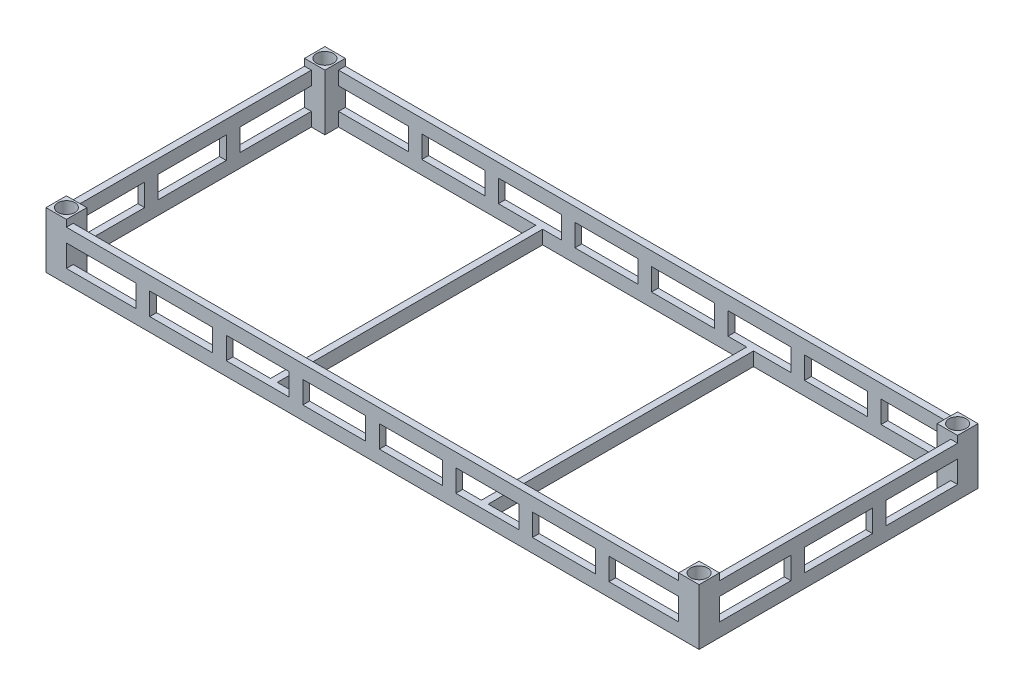
SolidWorks part; units mm, degrees
ref_plane "Front Plane" through (0, 0, 0) normal (0, 0, 1) x (1, 0, 0)
ref_plane "Top Plane" through (0, 0, 0) normal (0, 1, 0) x (1, 0, 0)
ref_plane "Right Plane" through (0, 0, 0) normal (1, 0, 0) x (0, 0, -1)
sketch "Sketch1" plane through (0, 0, 0) normal (0, 1, 0) x (1, 0, 0)
  line L0 (0, 820) -> (60, 820)
  line L1 (0, 0) -> (1920, 0)
  line L2 (0, 0) -> (0, 820)
  line L3 (0, 820) -> (1920, 820)
  line L4 (1920, 0) -> (1920, 820)
  line L5 (60, 820) -> (60, 760)
  line L6 (60, 760) -> (0, 760)
  line L7 (0, 760) -> (0, 765)
  line L8 (0, 765) -> (60, 765)
  line L9 (60, 765) -> (55, 765)
  line L10 (55, 765) -> (55, 820)
  line L11 (55, 820) -> (55, 815)
  line L12 (55, 815) -> (0, 815)
  line L13 (0, 815) -> (5, 815)
  line L14 (5, 815) -> (5, 765)
  line L15 (0, 760) -> (60, 820)
  line L16 (960, 0) -> (960, 820)
  line L17 (960, 820) -> (960, 0)
  line L18 (960, 410) -> (0, 410)
  line L19 (1920, 760) -> (1860, 820)
  line L20 (1915, 815) -> (1915, 765)
  line L21 (1920, 815) -> (1915, 815)
  line L22 (1865, 815) -> (1920, 815)
  line L23 (1865, 820) -> (1865, 815)
  line L24 (1865, 765) -> (1865, 820)
  line L25 (1860, 765) -> (1865, 765)
  line L26 (1920, 765) -> (1860, 765)
  line L27 (1920, 760) -> (1920, 765)
  line L28 (1860, 760) -> (1920, 760)
  line L29 (1860, 820) -> (1860, 760)
  line L30 (1920, 820) -> (1860, 820)
  line L31 (1920, 0) -> (1860, 0)
  line L32 (1860, 0) -> (1860, 60)
  line L33 (1860, 60) -> (1920, 60)
  line L34 (1920, 60) -> (1920, 55)
  line L35 (1920, 55) -> (1860, 55)
  line L36 (1860, 55) -> (1865, 55)
  line L37 (1865, 55) -> (1865, 0)
  line L38 (1865, 0) -> (1865, 5)
  line L39 (1865, 5) -> (1920, 5)
  line L40 (1920, 5) -> (1915, 5)
  line L41 (1915, 5) -> (1915, 55)
  line L42 (1920, 60) -> (1860, 0)
  line L43 (0, 60) -> (60, 0)
  line L44 (5, 5) -> (5, 55)
  line L45 (0, 5) -> (5, 5)
  line L46 (55, 5) -> (0, 5)
  line L47 (55, 0) -> (55, 5)
  line L48 (55, 55) -> (55, 0)
  line L49 (60, 55) -> (55, 55)
  line L50 (0, 55) -> (60, 55)
  line L51 (0, 60) -> (0, 55)
  line L52 (60, 60) -> (0, 60)
  line L53 (60, 0) -> (60, 60)
  line L54 (0, 0) -> (1920, 0)
  line L55 (0, 0) -> (60, 0)
  line L56 (60, 0) -> (60, 20)
  line L57 (60, 20) -> (1860, 20)
  line L58 (1920, 60) -> (1900, 60)
  line L59 (1900, 60) -> (1900, 760)
  line L60 (60, 800) -> (1860, 800)
  line L61 (20, 60) -> (20, 760)
  circle A0 centre (30, 790) radius 25
  circle A1 centre (1890, 790) radius 25
  circle A2 centre (1890, 30) radius 25
  circle A3 centre (30, 30) radius 25
extrude "Boss-Extrude1" add sketch "Sketch1" along normal blind 165 contours L14 L12 L2 L8 | A0 L14 L15 | A0 L15 L8 | L2 L15 L8 | L15 L6 L5 L8 | A0 L8 L10 | L15 L10 L8 L5 | A0 L12 L14 | L12 L10 L0 L2 | A0 L15 L12 | A0 L10 L15 | L10 L15 L3 | L5 L60 L16 L3 | L18 L61 L6 L2 | L52 L61 L18 L2 | L2 L50 L43 | L50 L2 L45 L44 | L49 L53 L52 L43 L50 | L43 A3 L50 | L44 A3 L43 | L50 A3 L48 | L43 L53 L49 L48 | L43 A3 L46 | L48 A3 L43 | L1 L47 L46 L45 L2 | L47 L1 L43 | L46 A3 L44 | L57 L53 L1 L16 | L57 L16 L1 L32 | L42 L37 L35 L32 | A2 L37 L42 | A2 L42 L39 | L37 L42 L1 | L39 L37 L31 L4 | A2 L39 L41 | L41 L39 L4 L35 | L42 L33 L32 L35 | A2 L35 L37 | A2 L42 L35 | L4 L42 L35 | A2 L41 L42 | L59 L33 L4 L28 | L25 L29 L28 L19 L26 | L4 L26 L19 | L20 A1 L19 | L19 A1 L26 | L26 L4 L21 L20 | L3 L23 L22 L21 L4 | L22 A1 L20 | L23 L3 L19 | L19 L29 L25 L24 | L24 A1 L19 | L19 A1 L22 | L26 A1 L24 | L16 L60 L29 L3
sketch "Sketch2" plane through (0, 0, 0) normal (0, 0, 1) x (1, 0, 0)
  line L0 (0, 165) -> (60, 165)
  line L1 (0, 165) -> (1920, 165) construction
  line L2 (60, 165) -> (60, 145)
  line L3 (60, 145) -> (1860, 145)
  line L4 (1860, 145) -> (1860, 165)
  line L5 (1860, 165) -> (60, 165)
  line L6 (1860, 145) -> (1860, 105)
  line L7 (1860, 105) -> (60, 105)
  line L8 (60, 105) -> (60, 145)
  line L9 (60, 105) -> (60, 40)
  line L10 (60, 40) -> (1860, 40)
  line L11 (1860, 105) -> (1860, 40)
  line L12 (960, 105) -> (960, 40)
  line L13 (960, 40) -> (980, 40)
  line L14 (980, 40) -> (980, 105)
  line L15 (980, 105) -> (940, 105)
  line L16 (940, 105) -> (940, 40)
  line L17 (960, 105) -> (1860, 105)
  line L18 (1860, 105) -> (1410, 105)
  line L19 (960, 105) -> (1410, 105)
  line L20 (1185, 105) -> (1185, 40)
  line L21 (1185, 40) -> (1410, 40)
  line L22 (1410, 40) -> (1410, 105)
  line L23 (1635, 105) -> (1635, 40)
  line L24 (960, 105) -> (735, 105)
  line L25 (735, 105) -> (735, 40)
  line L26 (735, 40) -> (510, 40)
  line L27 (510, 40) -> (510, 105)
  line L28 (510, 105) -> (285, 105)
  line L29 (285, 105) -> (285, 40)
  line L30 (755, 40) -> (755, 105)
  line L31 (755, 105) -> (715, 105)
  line L32 (735, 40) -> (755, 40)
  line L33 (715, 105) -> (715, 40)
  line L34 (735, 105) -> (735, 40)
  line L35 (530, 40) -> (530, 105)
  line L36 (530, 105) -> (490, 105)
  line L37 (510, 40) -> (530, 40)
  line L38 (490, 105) -> (490, 40)
  line L39 (510, 105) -> (510, 40)
  line L40 (305, 40) -> (305, 105)
  line L41 (305, 105) -> (265, 105)
  line L42 (285, 40) -> (305, 40)
  line L43 (265, 105) -> (265, 40)
  line L44 (285, 105) -> (285, 40)
  line L45 (1205, 40) -> (1205, 105)
  line L46 (1205, 105) -> (1165, 105)
  line L47 (1185, 40) -> (1205, 40)
  line L48 (1165, 105) -> (1165, 40)
  line L49 (1185, 105) -> (1185, 40)
  line L50 (1430, 40) -> (1430, 105)
  line L51 (1430, 105) -> (1390, 105)
  line L52 (1410, 40) -> (1430, 40)
  line L53 (1390, 105) -> (1390, 40)
  line L54 (1410, 105) -> (1410, 40)
  line L55 (1655, 40) -> (1655, 105)
  line L56 (1655, 105) -> (1615, 105)
  line L57 (1635, 40) -> (1655, 40)
  line L58 (1615, 105) -> (1615, 40)
  line L59 (1635, 105) -> (1635, 40)
  line M7 (1920, 165) -> (0, 165)
extrude "Cut-Extrude1" cut sketch "Sketch2" against normal through all both and the other way through all contours L43 L7 L9 L10 | L40 L10 L38 L28 | L35 L26 L33 L7 | L30 L10 L16 L7 | L48 L17 L14 L10 | L53 L19 L45 L21 | L58 L7 L50 L10 | L55 L10 L11 L7 | L3 L4 L2 M7
sketch "Sketch3" plane through (1920, 0, 0) normal (1, 0, 0) x (0, 0, -1)
  line L0 (820, 165) -> (760, 165)
  line L1 (0, 165) -> (820, 165) construction
  line L2 (760, 165) -> (760, 0)
  line L3 (760, 0) -> (60, 0)
  line L4 (0, 0) -> (820, 0) construction
  line L5 (60, 0) -> (60, 165)
  line L6 (60, 165) -> (760, 165)
  line L7 (60, 165) -> (60, 145)
  line L8 (60, 145) -> (760, 145)
  line L9 (410, 145) -> (310, 145)
  line L10 (310, 145) -> (310, 0)
  line L11 (310, 0) -> (270, 0)
  line L12 (270, 0) -> (270, 145)
  line L13 (410, 145) -> (410, 212.6198)
  line L14 (510, 145) -> (510, 0)
  line L15 (550, 0) -> (550, 145)
  line L16 (760, 145) -> (760, 105)
  line L17 (760, 105) -> (60, 105)
  line L18 (60, 105) -> (60, 40)
  line L19 (60, 40) -> (760, 40)
  line M9 (820, 165) -> (0, 165)
extrude "Cut-Extrude2" cut sketch "Sketch3" against normal through all both and the other way through all contours L8 L13 L6 L5 | L13 L8 L2 M9 | L10 L19 L14 L17 | L15 L19 L2 L17 | L5 L19 L12 L17
sketch "Sketch5" plane through (0, 0, 0) normal (0, -1, 0) x (1, 0, 0)
  line L0 (960, 0) -> (1260, 0)
  line L1 (0, 0) -> (1920, 0) construction
  line L2 (1260, 0) -> (1260, -820)
  line L3 (0, -820) -> (1920, -820) construction
  line L4 (1260, -820) -> (1280, -820)
  line L5 (1280, -820) -> (1280, 0)
  line L6 (1280, 0) -> (1260, 0)
  line L7 (960, 0) -> (660, 0)
  line L8 (660, 0) -> (660, -820)
  line L9 (660, -820) -> (640, -820)
  line L10 (640, -820) -> (640, 0)
  line L11 (640, 0) -> (660, 0)
  line M11 (1860, -800) -> (60, -800)
  line M17 (60, -20) -> (1860, -20)
extrude "Boss-Extrude3" add sketch "Sketch5" against normal blind 40 contours L10 L8 M11 M17 | L5 L2 M11 M17
scale "Scale2" scale about centroid uniform scaling yes scale factor 0.1
